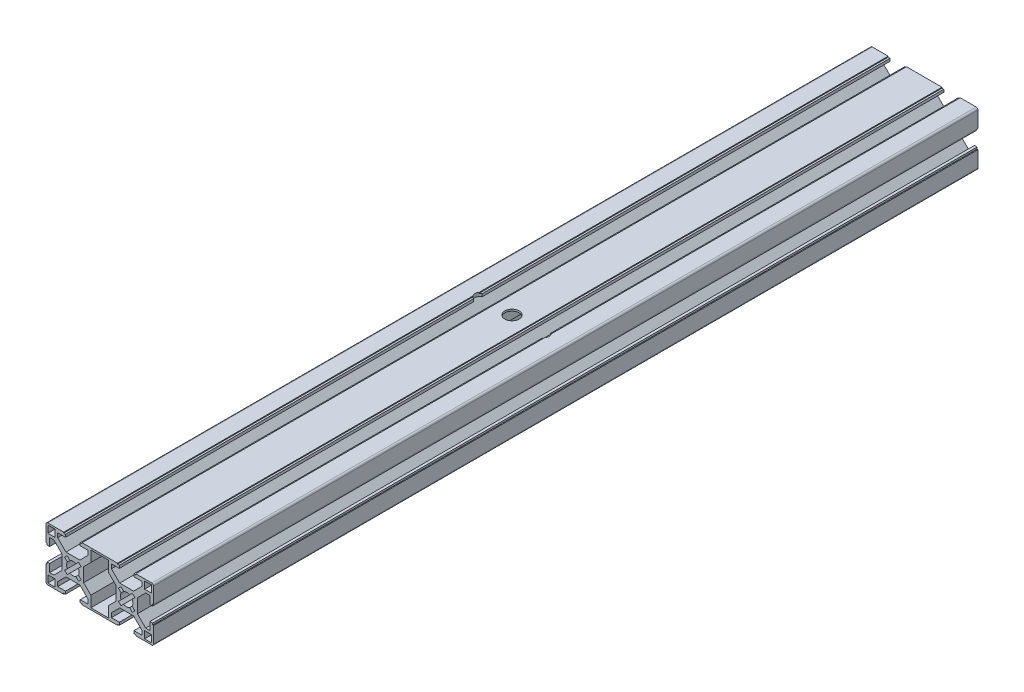
SolidWorks part; units mm, degrees
material "6063-O"
ref_plane "Plano frontal" through (0, 0, 0) normal (0, 0, 1) x (1, 0, 0)
ref_plane "Plano superior" through (0, 0, 0) normal (0, 1, 0) x (1, 0, 0)
ref_plane "Plano direito" through (0, 0, 0) normal (1, 0, 0) x (0, 0, -1)
sketch "Esboço1" plane through (0, 0, 0) normal (0, 0, 1) x (1, 0, 0)
  line L5 (0, 0) -> (-17.7944, 17.7944) construction
  line L6 (0, 3.5) -> (0, 6)
  line L8 (0, 6) -> (-3.8787, 6)
  line L9 (-3.5, 0) -> (-6, 0)
  line L48 (-6, 0) -> (-6, 3.8787)
  line L49 (-3.8787, 6) -> (-8.5, 10.6213)
  line L50 (-6, 3.8787) -> (-10.6213, 8.5)
  line L51 (0, 0) -> (-12.921, 0) construction
  line L52 (-8.5, 13) -> (-4.1, 13)
  line L53 (-4.1, 13) -> (-4.1, 14.5)
  line L54 (-4.1, 14.5) -> (-5.1, 14.5)
  line L55 (-5.1, 14.5) -> (-5.1, 15)
  line L56 (-5.1, 15) -> (-15, 15)
  line L57 (-15, 5.1) -> (-15, 15)
  line L58 (-14.5, 5.1) -> (-15, 5.1)
  line L59 (-14.5, 4.1) -> (-14.5, 5.1)
  line L60 (-13, 4.1) -> (-14.5, 4.1)
  line L61 (-13, 8.5) -> (-13, 4.1)
  line L62 (-1.6646, 3.0788) -> (-3.182, 4.5962)
  line L63 (-3.0788, 1.6646) -> (-4.5962, 3.182)
  line L64 (-4.5962, 3.182) -> (-3.182, 4.5962)
  line L65 (-8.5, 13) -> (-8.5, 10.6213)
  line L66 (-10, 14) -> (-14, 14)
  line L67 (-10, 14) -> (-10, 10)
  line L68 (-10, 10) -> (-14, 10)
  line L69 (-14, 14) -> (-14, 10)
  line L70 (-10, 14) -> (-14, 10) construction
  line L71 (-10, 10) -> (-14, 14) construction
  line L72 (-13, 8.5) -> (-10.6213, 8.5)
  circle A1 centre (0, 0) radius 3.5
  point P25 (-12, 12)
  dimension "D5" = 10.9
  dimension "D9" = 5.5
  dimension "D10" = 2
  dimension "D11" = 4
  dimension "D12" = 4
  dimension "D13" = 1
  dimension "D1" = 7
  dimension "D2" = 6
  dimension "D3" = 3
  dimension "D4" = 9.9
  dimension "D6" = 0.5
  dimension "D7" = 1.5
  dimension "D8" = 15
  dimension "D14" = 6.5
extrude "Ressalto-extrusão1" add sketch "Esboço1" along normal blind 460 contours A1 L6 L8 L49 L65 L52 L53 L54 L55 L56 L57 L58 L59 L60 L61 L72 L50 L48 L9 L63 L64 L62 L69 L66 L67 L68
sketch "Esboço3" plane through (0, 0, 0) normal (1, 0, 0) x (0, 0, -1)
  line L0 (0, 0) -> (-1000, 0) construction
  dimension "D1" = 1000
pattern_circular "PadrãoCircular1" count 4 over 360 about axis through (0, 0, 0) along (0, 0, 1) of "Ressalto-extrusão1"
pattern_linear "Padrão linear1" count 2 spacing 30 along (1, 0, 0) of "Ressalto-extrusão1", "PadrãoCircular1"
sketch "Esboço4" plane through (0, 0, 0) normal (0, 0, -1) x (-1, 0, 0)
  line L0 (-20, 14) -> (-20, -14)
  line L1 (-20, -14) -> (-10, -14)
  line L2 (-10, -14) -> (-10, 14)
  line L3 (-10, 14) -> (-20, 14)
extrude "Corte-extrusão1" cut sketch "Esboço4" against normal through all
fillet "Filete1" radius 1 4 edges at (45, -15, 230) (45, 15, 230) (-15, 15, 230) (-15, -15, 230)
sketch "Esboço5" plane through (0, 15, 0) normal (0, 1, 0) x (1, 0, 0)
  line L0 (15, 0) -> (15, -460) construction
  line L1 (5.1, 0) -> (24.9, 0) construction
  line L2 (5.1, -460) -> (24.9, -460) construction
  circle A0 centre (15, -230) radius 4
  dimension "D1" = 8
extrude "Corte-extrusão2" cut sketch "Esboço5" against normal blind 10
ref_plane "Plane1" through (0, 0, 230) normal (0, 0, -1) x (-1, 0, 0)
sketch "Sketch2" plane through (0, 15, 0) normal (0, 1, 0) x (1, 0, 0)
  line L0 (15, -230) -> (33.25, -230) construction
  line L1 (15, -230) -> (15, -245.477) construction
  circle A0 centre (33.25, -230) radius 2.5
  circle A1 centre (-3.25, -230) radius 2.5
  dimension "D1" = 5
  dimension "D2" = 36.5
extrude "Cut-Extrude1" cut sketch "Sketch2" against normal blind 3
